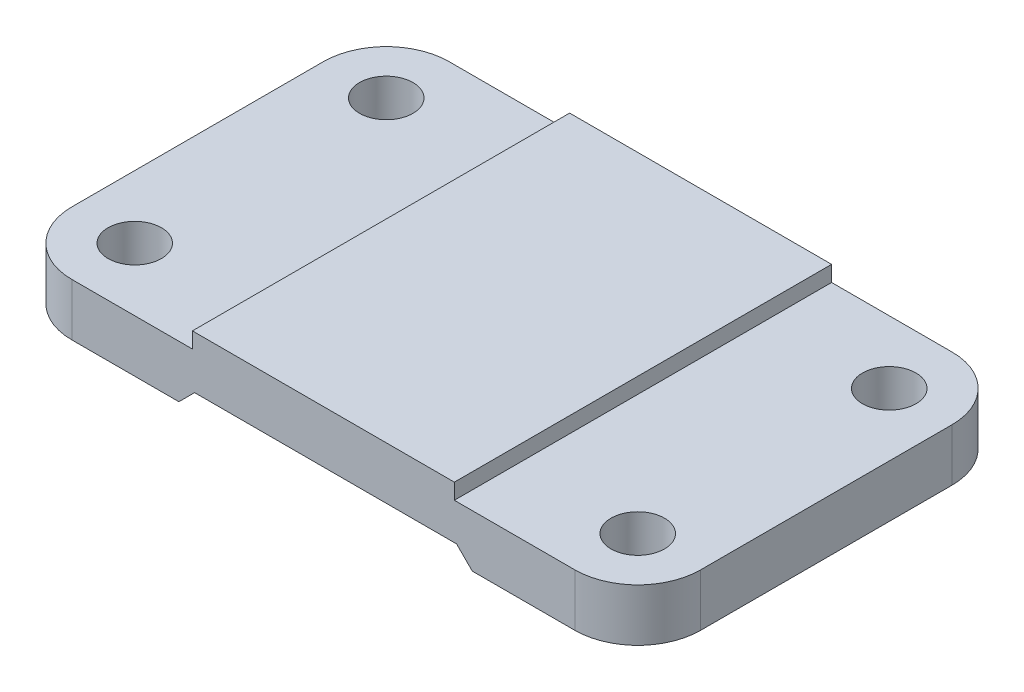
SolidWorks part; units mm, degrees
material "1.0044 (S275JR)"
ref_plane "Alzado" through (0, 0, 0) normal (0, 0, 1) x (1, 0, 0)
ref_plane "Planta" through (0, 0, 0) normal (0, 1, 0) x (1, 0, 0)
ref_plane "Vista lateral" through (0, 0, 0) normal (1, 0, 0) x (0, 0, -1)
sketch "Croquis1" plane through (0, 0, 0) normal (0, 0, 1) x (1, 0, 0)
  line L0 (0, 0) -> (0, 10)
  line L1 (0, 10) -> (35, 10)
  line L2 (35, 10) -> (35, 13)
  line L3 (35, 13) -> (85, 13)
  line L4 (85, 13) -> (85, 10)
  line L5 (85, 10) -> (120, 10)
  line L6 (120, 10) -> (120, 0)
  line L7 (120, 0) -> (88.4207, 0)
  line L8 (88.4207, 0) -> (76.5929, 0) construction
  line L9 (88.4207, 0) -> (85.4207, 3)
  line L10 (85.4207, 3) -> (35.4207, 3)
  line L11 (35.4207, 3) -> (32.4207, 0)
  line L12 (32.4207, 0) -> (0, 0)
  dimension "D1" = 45
  dimension "D2" = 3
  dimension "D3" = 56
  dimension "D4" = 120
  dimension "D5" = 50
  dimension "D6" = 3
  dimension "D7" = 10
extrude "Saliente-Extruir1" add sketch "Croquis1" along normal blind 72
sketch "Croquis2" plane through (0, 10, 0) normal (0, 1, 0) x (1, 0, 0)
  circle A0 centre (12, -12) radius 5.1
  circle A1 centre (12, -60) radius 5.1
  circle A2 centre (108, -60) radius 5.1
  circle A3 centre (108, -12) radius 5.1
extrude "Cortar-Extruir1" cut sketch "Croquis2" against normal up to body
fillet "Redondeo1" radius 12 4 edges at (0, 5, 0) (120, 5, 0) (120, 5, 72) (0, 5, 72)
